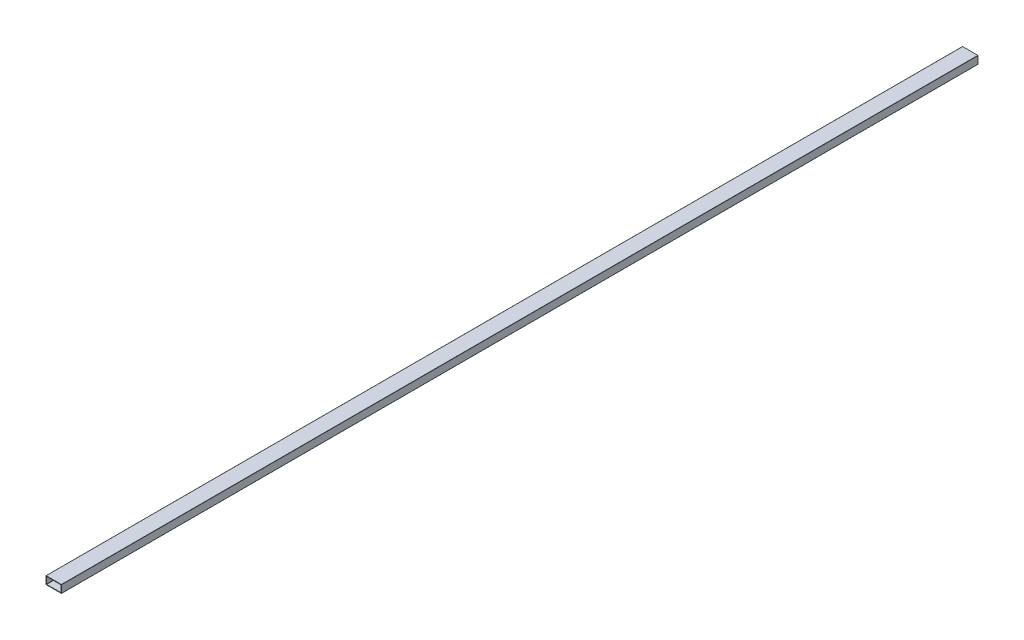
SolidWorks part; units mm, degrees
material "AISI 1035 Acero (SS)"
ref_plane "Alzado" through (0, 0, 0) normal (0, 0, 1) x (1, 0, 0)
ref_plane "Planta" through (0, 0, 0) normal (0, 1, 0) x (1, 0, 0)
ref_plane "Vista lateral" through (0, 0, 0) normal (1, 0, 0) x (0, 0, -1)
sketch "Croquis1" plane through (0, 0, 0) normal (0, 0, 1) x (1, 0, 0)
  line L0 (-47.76, -22.36) -> (-47.76, 22.36)
  line L1 (-50.8, -25.4) -> (50.8, -25.4)
  line L2 (-50.8, -25.4) -> (-50.8, 25.4)
  line L3 (-50.8, 25.4) -> (50.8, 25.4)
  line L4 (50.8, -25.4) -> (50.8, 25.4)
  line L5 (-50.8, -25.4) -> (50.8, 25.4) construction
  line L6 (-50.8, 25.4) -> (50.8, -25.4) construction
  line L7 (-47.76, 22.36) -> (47.76, 22.36)
  line L8 (47.76, -22.36) -> (47.76, 22.36)
  line L9 (-47.76, -22.36) -> (47.76, -22.36)
  point P0 (0, 0)
  dimension "D1" = 50.8
  dimension "D2" = 101.6
  dimension "D3" = 3.04
extrude "Saliente-Extruir1" add sketch "Croquis1" against normal blind 6000
fillet "Redondeo1" radius 1 8 edges at (-47.76, 22.36, -3000) (47.76, 22.36, -3000) (47.76, -22.36, -3000) (-50.8, -25.4, -3000) (-50.8, 25.4, -3000) (-47.76, -22.36, -3000) (50.8, -25.4, -3000) (50.8, 25.4, -3000)
